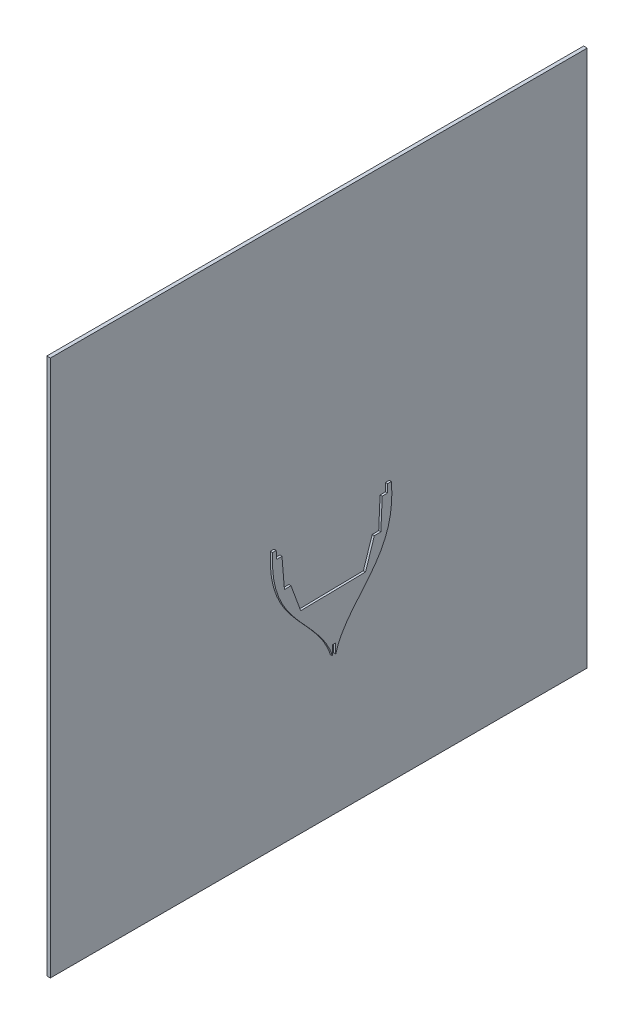
SolidWorks part; units mm, degrees
ref_plane "Plan de face" through (0, 0, 0) normal (0, 0, 1) x (1, 0, 0)
ref_plane "Plan de dessus" through (0, 0, 0) normal (0, 1, 0) x (1, 0, 0)
ref_plane "Plan de droite" through (0, 0, 0) normal (1, 0, 0) x (0, 0, -1)
sketch "Esquisse1" plane through (0, 0, 0) normal (0, 0, 1) x (1, 0, 0)
  point P0 (-20, 0)
  dimension "D1" = 20
sketch3d "Esquisse3D1"
  line L1 (-20, 1121.2893, 777.275) -> (-20, 1121.2893, -722.725)
  line L2 (-20, 1121.2893, 777.275) -> (-20, -378.7107, 777.275)
  line L3 (-20, -378.7107, 777.275) -> (-20, -378.7107, -722.725)
  line L4 (-20, 1121.2893, -722.725) -> (-20, -378.7107, -722.725)
  dimension "D1" = 1500
  dimension "D2" = 1500
extrude "Boss.-Extru.2" add sketch "Esquisse3D1" along direction (1, 0, 0) on the side of the normal blind 10 contours L2 L1 L4 L3
sketch "Esquisse4" plane through (-10, 0, 0) normal (1, 0, 0) x (0, 0, -1)
  line L0 (0, 0) -> (-7.701, 425.1082) construction
  line L1 (169.3944, 339.9131) -> (-188.5193, 333.4294) construction
  line L2 (-187.2006, 249.23) -> (169.0622, 255.6839) construction
  line L3 (-144.268, 175.2448) -> (126.4811, 180.1495) construction
sketch "Esquisse5" plane through (0, 0, 0) normal (1, 0, 0) x (0, 0, -1)
  line L0 (-7.701, 425.1082) -> (0, 0) construction
  line L2 (0, 0) -> (2.7718, 34.1548) construction
  line L3 (2.7718, 34.1548) -> (28.2815, 146.3034) construction
  line L4 (28.2815, 146.3034) -> (178.2749, 155.2949) construction
  line L5 (178.2749, 155.2949) -> (159.3623, 362.2903) construction
  line L8 (159.3623, 362.2903) -> (149.3623, 362.1091)
  line L9 (149.3623, 362.1091) -> (148.4773, 339.5342)
  line L10 (169.3944, 339.9131) -> (-188.5193, 333.4294) construction
  line L11 (148.4773, 339.5342) -> (133.9444, 339.2709)
  line L12 (133.9444, 339.2709) -> (130.1239, 254.9785)
  line L13 (-187.2006, 249.23) -> (169.0622, 255.6839) construction
  line L14 (130.1239, 254.9785) -> (111.9008, 254.6484)
  line L15 (111.9008, 254.6484) -> (87.362, 179.4408)
  line L16 (-144.268, 175.2448) -> (126.4811, 180.1495) construction
  line L17 (87.362, 179.4408) -> (-93.8038, 176.1589)
  line L18 (0, 0) -> (-4.0071, 34.032) construction
  line L19 (-4.0071, 34.032) -> (-33.5618, 145.1831) construction
  line L20 (-33.5618, 145.1831) -> (-183.7826, 148.7361) construction
  line L21 (-183.7826, 148.7361) -> (-172.3795, 356.2806) construction
  line L22 (-121.0504, 250.4284) -> (-93.8038, 176.1589)
  line L23 (-139.2735, 250.0983) -> (-121.0504, 250.4284)
  line L24 (-146.1445, 334.197) -> (-139.2735, 250.0983)
  line L25 (-160.6774, 333.9337) -> (-146.1445, 334.197)
  line L26 (-162.3795, 356.4618) -> (-160.6774, 333.9337)
  line L27 (-172.3795, 356.2806) -> (-162.3795, 356.4618)
  spline S0 degree 4 poles (0, 0) (2.7718, 34.1548) (28.2815, 146.3034) (178.2749, 155.2949) (159.3623, 362.2903) knots 0 0 0 0 0 1 1 1 1 1
  spline S1 degree 4 poles (0, 0) (-4.0071, 34.032) (-33.5618, 145.1831) (-183.7826, 148.7361) (-172.3795, 356.2806) knots 0 0 0 0 0 1 1 1 1 1
  point P30 (-3.2209, 177.7999)
  dimension "D1" = 10
extrude "Boss.-Extru.3" add sketch "Esquisse5" along normal blind 6 separate body
sketch "Esquisse6" plane through (6, 0, 0) normal (1, 0, 0) x (0, 0, -1)
  line L0 (-4.9085, 22.4711) -> (-5.3977, 49.4711)
  line L1 (-5.3977, 49.4711) -> (3.6023, 49.6342)
  line L2 (3.6023, 49.6342) -> (4.0915, 22.6342)
  line L3 (4.0915, 22.6342) -> (117.0633, -47.527)
  line L4 (117.0633, -47.527) -> (-85.2277, -65.22)
  line L5 (-85.2277, -65.22) -> (-4.9085, 22.4711)
  line L6 (-4.9085, 22.4711) -> (4.0915, 22.6342) construction
  line L7 (-144.268, 175.2448) -> (126.4811, 180.1495) construction
  spline S0 degree 4 poles (-172.3795, 356.2806) (-183.7826, 148.7361) (-33.5618, 145.1831) (-4.0071, 34.032) (0, 0) knots 0 0 0 0 0 1 1 1 1 1 construction
  spline S1 degree 4 poles (0, 0) (2.7718, 34.1548) (28.2815, 146.3034) (178.2749, 155.2949) (159.3623, 362.2903) knots 0 0 0 0 0 1 1 1 1 1 construction
  dimension "D1" = 9
  dimension "D2" = 27
extrude "Enlèv. mat.-Extru.1" cut sketch "Esquisse6" against normal blind 6
